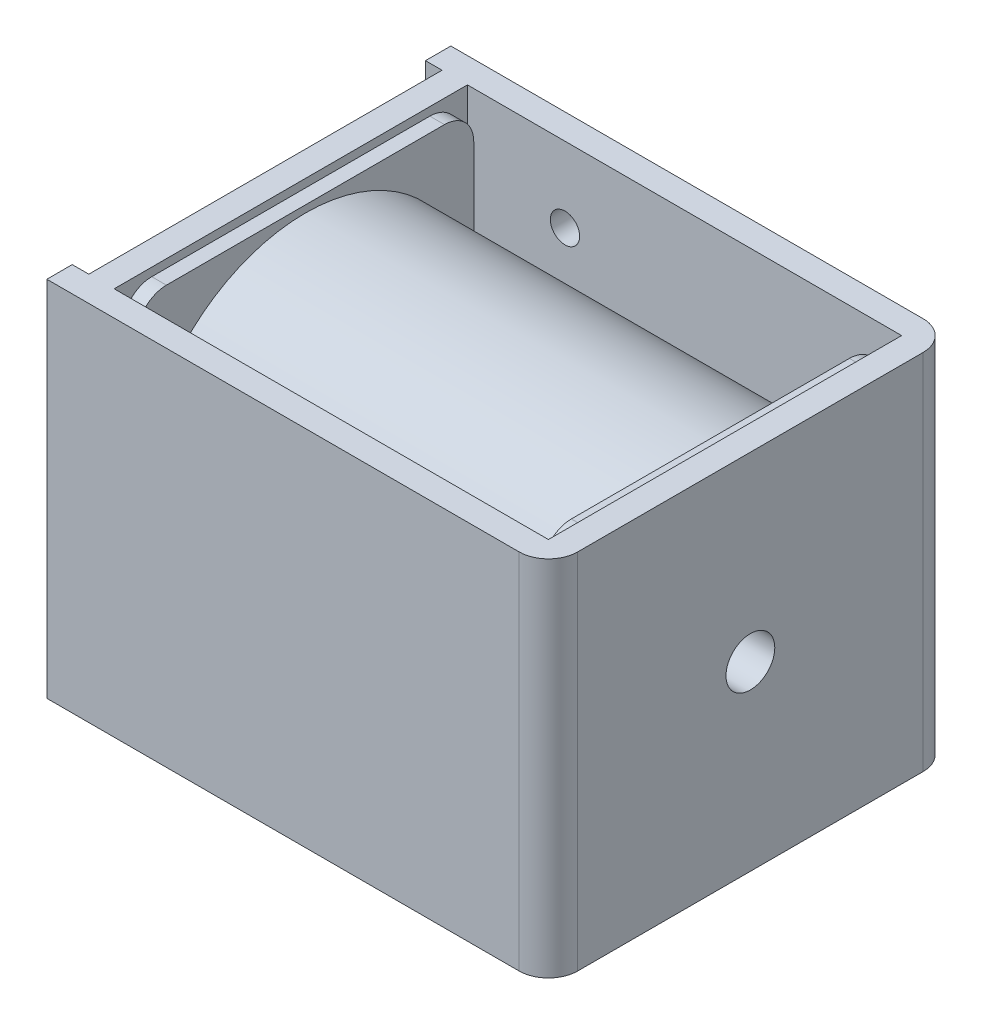
SolidWorks part; units mm, degrees
ref_plane "Alzado" through (0, 0, 0) normal (0, 0, 1) x (1, 0, 0)
ref_plane "Planta" through (0, 0, 0) normal (0, 1, 0) x (1, 0, 0)
ref_plane "Vista lateral" through (0, 0, 0) normal (1, 0, 0) x (0, 0, -1)
sketch "Croquis1" plane through (0, 0, 0) normal (0, 1, 0) x (1, 0, 0)
  line L1 (2.6, 0) -> (47.1, 0)
  line L2 (0, 0) -> (0, -36.2)
  line L3 (2.6, -36.2) -> (47.1, -36.2)
  line L4 (47.1, 0) -> (47.1, -36.2)
  line L5 (-1.7, -38.8) -> (49.7, -38.8)
  line L6 (49.7, 2.6) -> (49.7, -38.8)
  line L7 (-1.7, 2.6) -> (49.7, 2.6)
  line L8 (0, 0) -> (-1.7, 0)
  line L9 (-1.7, 0) -> (-1.7, 2.6)
  line L10 (0, -36.2) -> (-1.7, -36.2)
  line L11 (-1.7, -36.2) -> (-1.7, -38.8)
  line L12 (2.6, 0) -> (2.6, -36.2)
  line L14 (-2.6, 2.6) -> (-2.6, -38.8) construction
  line L15 (-2.6, 2.6) -> (49.7, 2.6) construction
  line L16 (-2.6, -38.8) -> (49.7, -38.8) construction
  line L17 (0, 0) -> (47.1, 0) construction
  line L18 (0, -36.2) -> (47.1, -36.2) construction
  dimension "D2" = 41.4
  dimension "D3" = 51.4
  dimension "D4" = 1.7
  dimension "D5" = 1.7
  dimension "D6" = 2.6
  dimension "D1" = 2.6
extrude "Saliente-Extruir1" add sketch "Croquis1" along normal blind 37.2
sketch "Croquis2" plane through (0, 0, 0) normal (-1, 0, 0) x (0, 0, 1)
  line L0 (0, 18.6) -> (36.2, 18.6) construction
  line L4 (0, 0) -> (36.2, 0)
  line L5 (36.2, 0) -> (36.2, 37.2)
  line L6 (36.2, 37.2) -> (0, 37.2)
  line L7 (0, 37.2) -> (0, 0)
  line L8 (0, 0) -> (36.2, 0)
  line L9 (36.2, 0) -> (36.2, 37.2)
  line L10 (36.2, 37.2) -> (0, 37.2)
  line L11 (0, 37.2) -> (0, 0)
  circle A0 centre (18.1, 18.6) radius 17.0288
  point P8 (18.1, 18.6)
  line M7 (36.2, 0) -> (36.2, 37.2)
  line M9 (0, 37.2) -> (0, 0)
  dimension "D1" = 0
extrude "Saliente-Extruir2" add sketch "Croquis2" against normal up to surface (47.1 mm away) contours L0 A0 L9 M9 | L11 L0 A0 M7 up to face at (47.1, 18.6, 18.1)
sketch "Croquis3" plane through (2.6, 0, 0) normal (1, 0, 0) x (0, 0, -1)
  line L0 (-32.35, 0.85) -> (-3.85, 0.85)
  line L1 (-0.85, 3.85) -> (-0.85, 33.35)
  line L2 (-3.85, 36.35) -> (-32.35, 36.35)
  line L3 (-35.35, 33.35) -> (-35.35, 3.85)
  line L4 (-36.2, 0) -> (0, 0)
  line L5 (0, 0) -> (0, 37.2)
  line L6 (0, 37.2) -> (-36.2, 37.2)
  line L7 (-36.2, 37.2) -> (-36.2, 0)
  line L8 (-36.2, 0) -> (0, 0)
  line L9 (0, 0) -> (0, 37.2)
  line L10 (0, 37.2) -> (-36.2, 37.2)
  line L11 (-36.2, 37.2) -> (-36.2, 0)
  line L12 (-35.35, 0.85) -> (-0.85, 0.85) construction
  line L13 (-0.85, 0.85) -> (-0.85, 36.35) construction
  line L14 (-35.35, 36.35) -> (-35.35, 0.85) construction
  line L15 (-0.85, 36.35) -> (-35.35, 36.35) construction
  arc A0 (-3.85, 0.85) -> (-0.85, 3.85) centre (-3.85, 3.85) ccw
  arc A1 (-32.35, 0.85) -> (-35.35, 3.85) centre (-32.35, 3.85) cw
  arc A2 (-32.35, 36.35) -> (-35.35, 33.35) centre (-32.35, 33.35) ccw
  arc A3 (-0.85, 33.35) -> (-3.85, 36.35) centre (-3.85, 33.35) ccw
  circle M13 centre (-18.1, 18.6) radius 17.0288
  dimension "D3" = 3
  dimension "D1" = 0
  dimension "D2" = 0.85
extrude "Saliente-Extruir3" add sketch "Croquis3" along normal blind 1.5 contours L1 A3 L2 A2 L3 A1 L0 A0 M13
ref_plane "Plano1" through (24.85, 0, 0) normal (1, 0, 0) x (0, 0, -1)
mirror "Simetría1" about plane through (24.85, 0, 0) normal (1, 0, 0) of "Saliente-Extruir3"
ref_plane "Plano2" through (0, 18.6, 0) normal (0, 1, 0) x (1, 0, 0)
sketch "Croquis4" plane through (0, 18.6, 0) normal (0, 1, 0) x (1, 0, 0)
  line L0 (49.7, -18.1) -> (0, -18.1)
  line L1 (49.7, -38.8) -> (49.7, 2.6) construction
  line L2 (0, 0) -> (0, -36.2) construction
  line L3 (49.7, -15.6) -> (49.7, -18.1)
  line L4 (0, -11.9) -> (32.7, -11.9)
  line L5 (0, -11.9) -> (0, -18.1)
  line L7 (32.7, -11.9) -> (32.7, -13.1)
  line L8 (49.7, -15.6) -> (36.9, -15.6)
  line L14 (32.7, -13.1) -> (36.9, -13.1)
  line L15 (36.9, -15.6) -> (36.9, -13.1)
  point P7 (34.8, -13.1)
  dimension "D1" = 6.2
  dimension "D2" = 32.7
  dimension "D3" = 2.5
  dimension "D4" = 5
  dimension "D5" = 36.9
revolve "Cortar-Revolución1" cut sketch "Croquis4" angle 360 about L0
fillet "Redondeo1" radius 3 1 edges at (49.7, 18.6, -2.6)
fillet "Redondeo2" radius 3 1 edges at (49.7, 18.6, 38.8)
sketch "Croquis5" plane through (0, 0, -2.6) normal (0, 0, -1) x (-1, 0, 0)
  line L1 (-42.1, 29.5) -> (-12.6, 29.5)
  line L2 (-42.1, 29.5) -> (-42.1, 7.7)
  line L3 (-42.1, 7.7) -> (-12.6, 7.7)
  line L4 (-12.6, 29.5) -> (-12.6, 7.7)
  line L5 (-42.1, 29.5) -> (-12.6, 7.7) construction
  line L6 (-42.1, 7.7) -> (-12.6, 29.5) construction
  line L9 (1.7, 18.6) -> (-46.7, 18.6) construction
  line L10 (1.7, 37.2) -> (1.7, 0) construction
  line L11 (-46.7, 37.2) -> (-46.7, 0) construction
  line L12 (-11.1, 29.5) -> (-11.1, 37.2) construction
  line L13 (-46.7, 37.2) -> (1.7, 37.2) construction
  circle A0 centre (-42.1, 29.5) radius 1.5
  circle A1 centre (-12.6, 29.5) radius 1.5
  circle A2 centre (-42.1, 7.7) radius 1.5
  circle A3 centre (-12.6, 7.7) radius 1.5
  point P0 (-27.35, 18.6)
  dimension "D1" = 3
  dimension "D2" = 12.8
  dimension "D3" = 21.8
  dimension "D4" = 29.5
extrude "Cortar-Extruir1" cut sketch "Croquis5" against normal up to surface (2.6 mm away) contours L1 A0 L2 | L2 A0 L1 | L2 A2 L3 | L3 A2 L2 | L4 A3 L3 | L1 A1 L4 | L4 A1 L1 up to face at (24.85, 18.6, 0)
ref_plane "Plano3" through (0, 0, 18.1) normal (0, 0, -1) x (-1, 0, 0)
